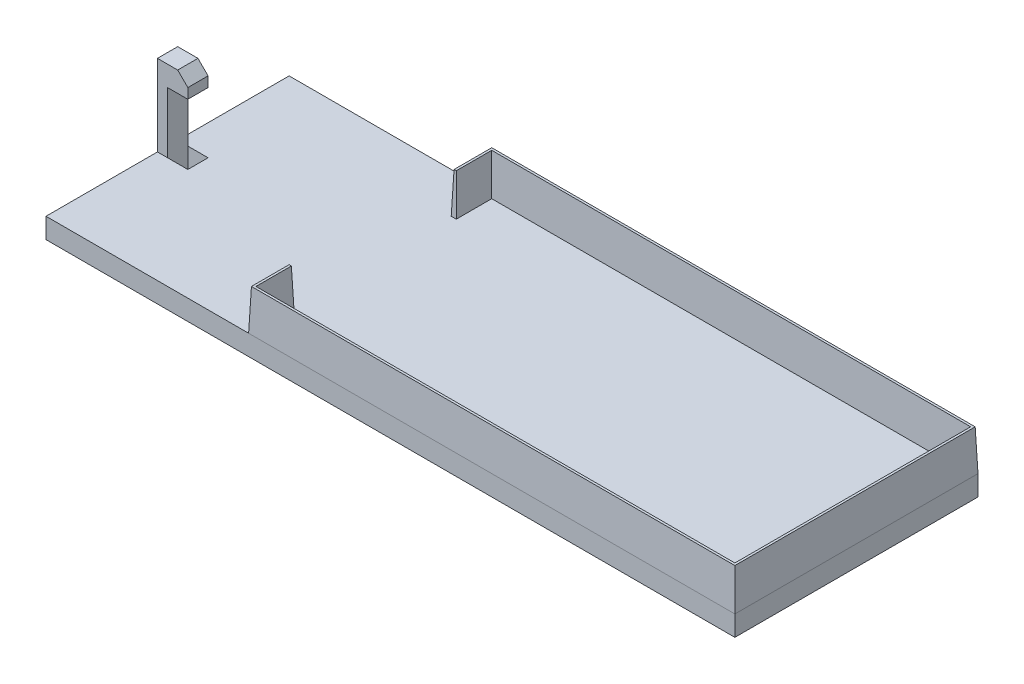
SolidWorks part; units mm, degrees
ref_plane "Front Plane" through (0, 0, 0) normal (0, 0, 1) x (1, 0, 0)
ref_plane "Top Plane" through (0, 0, 0) normal (0, 1, 0) x (1, 0, 0)
ref_plane "Right Plane" through (0, 0, 0) normal (1, 0, 0) x (0, 0, -1)
sketch "Sketch1" plane through (0, 0, 0) normal (0, 1, 0) x (1, 0, 0)
  line L1 (-107.95, -38.1) -> (107.95, -38.1)
  line L2 (-107.95, -38.1) -> (-107.95, 38.1)
  line L3 (-107.95, 38.1) -> (107.95, 38.1)
  line L4 (107.95, -38.1) -> (107.95, 38.1)
  line L5 (-107.95, -38.1) -> (107.95, 38.1) construction
  line L6 (-107.95, 38.1) -> (107.95, -38.1) construction
  point P0 (0, 0)
  dimension "D1" = 76.2
  dimension "D2" = 215.9
extrude "Boss-Extrude1" add sketch "Sketch1" along normal blind 6.35
sketch "Sketch2" plane through (0, 6.35, 0) normal (0, 1, 0) x (1, 0, 0)
  line L0 (-44.45, -38.1) -> (107.95, -38.1)
  line L1 (-107.95, -38.1) -> (107.95, -38.1) construction
  line L2 (107.95, -38.1) -> (107.95, 38.1)
  line L3 (107.95, 38.1) -> (-44.45, 38.1)
  line L4 (107.95, 38.1) -> (-107.95, 38.1) construction
  line L5 (-44.45, 38.1) -> (-44.45, 25.4)
  line L9 (-44.45, -25.4) -> (-44.45, -38.1)
  line L10 (-42.8625, -25.4) -> (-42.8625, -36.5125)
  line L11 (-42.8625, -36.5125) -> (106.3625, -36.5125)
  line L12 (106.3625, -36.5125) -> (106.3625, 36.5125)
  line L13 (106.3625, 36.5125) -> (-42.8625, 36.5125)
  line L14 (-42.8625, 36.5125) -> (-42.8625, 25.4)
  line L15 (-44.45, 25.4) -> (-42.8625, 25.4)
  line L16 (-44.45, -25.4) -> (-42.8625, -25.4)
  dimension "D2" = 152.4
  dimension "D3" = 12.7
  dimension "D1" = 1.5875
extrude "Boss-Extrude2" add sketch "Sketch2" along normal blind 12.7 draft 2
sketch "Sketch3" plane through (0, 0, 0) normal (0, 0, 1) x (1, 0, 0)
  line L0 (-107.95, 6.35) -> (-107.95, 31.75)
  line L1 (-107.95, 31.75) -> (-101.6, 31.75)
  line L2 (-101.6, 31.75) -> (-98.425, 28.575)
  line L3 (-98.425, 28.575) -> (-98.425, 25.4)
  line L4 (-98.425, 25.4) -> (-104.775, 25.4)
  line L5 (-104.775, 25.4) -> (-104.775, 6.35)
  line L6 (-107.95, 6.35) -> (-44.45, 6.35) construction
  line L7 (-104.775, 6.35) -> (-107.95, 6.35)
  dimension "D1" = 3.175
  dimension "D2" = 6.35
  dimension "D3" = 45
  dimension "D4" = 6.35
  dimension "D5" = 3.175
  dimension "D6" = 25.4
extrude "Boss-Extrude3" add sketch "Sketch3" along normal mid plane 6.35
sketch "Sketch4" plane through (0, 6.35, 0) normal (0, 1, 0) x (1, 0, 0)
  line L4 (-98.425, 3.175) -> (-104.775, 3.175)
  line L5 (-98.425, -3.175) -> (-98.425, 3.175)
  line L6 (-104.775, -3.175) -> (-98.425, -3.175)
  line L7 (-104.775, 3.175) -> (-104.775, -3.175)
  line L8 (-98.425, 3.175) -> (-104.775, 3.175)
  line L9 (-98.425, -3.175) -> (-98.425, 3.175)
  line L10 (-104.775, -3.175) -> (-98.425, -3.175)
  line L11 (-104.775, 3.175) -> (-104.775, -3.175)
  dimension "D1" = 0
extrude "Cut-Extrude1" cut sketch "Sketch4" against normal through all
sketch "Sketch6" [suppressed] plane through (0, 6.35, 0) normal (0, 1, 0) x (1, 0, 0)
  circle A0 centre (0, 0) radius 25.4
  dimension "D1" = 50.8
extrude "Boss-Extrude5" [suppressed] add sketch "Sketch6" along normal blind 6.35
sketch "Sketch7" [suppressed] plane through (0, 12.7, 0) normal (0, 1, 0) x (1, 0, 0)
  circle A0 centre (0, 0) radius 10.6749
extrude "Boss-Extrude6" [suppressed] add sketch "Sketch7" along normal blind 6.35
fillet "Fillet1" [suppressed] radius 2.54
fillet "Fillet2" [suppressed] radius 2.54
